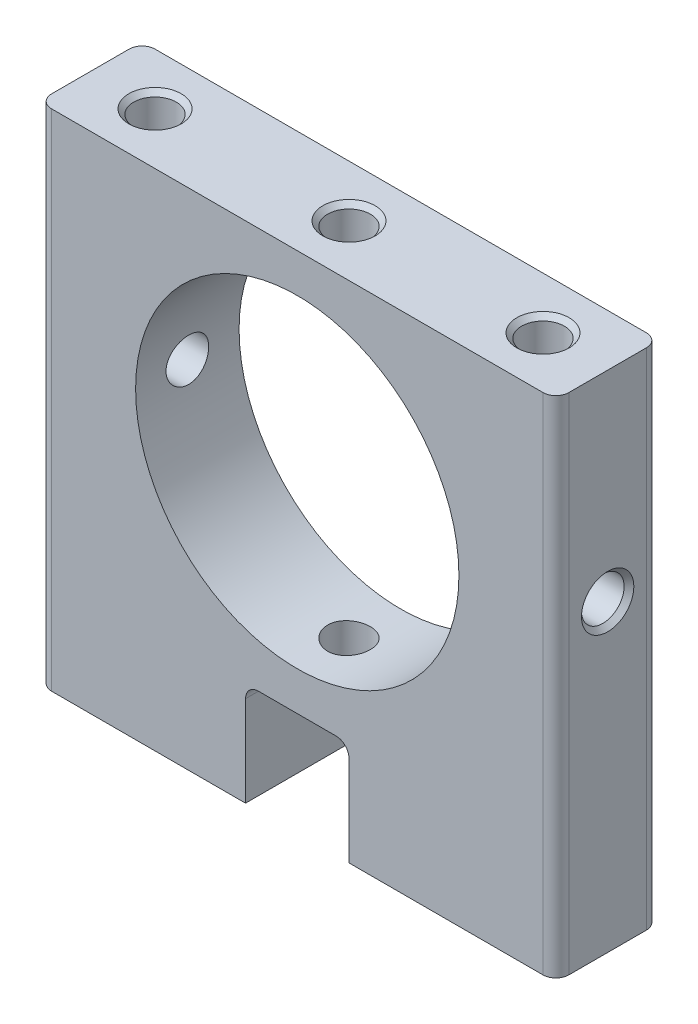
SolidWorks part; units mm, degrees
ref_plane "前视基准面" through (0, 0, 0) normal (0, 0, 1) x (1, 0, 0)
ref_plane "上视基准面" through (0, 0, 0) normal (0, 1, 0) x (1, 0, 0)
ref_plane "右视基准面" through (0, 0, 0) normal (1, 0, 0) x (0, 0, -1)
sketch "草图1" plane through (0, 0, 0) normal (0, 1, 0) x (1, 0, 0)
  line L1 (-20, 4) -> (20, 4)
  line L2 (-20, 4) -> (-20, -4)
  line L3 (-20, -4) -> (20, -4)
  line L4 (20, 4) -> (20, -4)
  line L5 (0, -4) -> (0, 4) construction
  line L6 (-20, 0) -> (20, 0) construction
  point P0 (0, 0)
  dimension "D1" = 8
  dimension "D2" = 40
extrude "凸台-拉伸1" add sketch "草图1" along normal blind 39
sketch "草图2" plane through (0, 39, 0) normal (0, 1, 0) x (1, 0, 0)
  line L0 (0, 4) -> (0, -4) construction
  line L1 (20, 4) -> (-20, 4) construction
  line L2 (-20, -4) -> (20, -4) construction
  line L3 (-20, 0) -> (20, 0) construction
  line L4 (-20, 4) -> (-20, -4) construction
  line L5 (20, -4) -> (20, 4) construction
  point P12 (-15, 0)
  point P13 (15, 0)
  dimension "D1" = 30
hole_wizard "M4 螺纹孔2" positions "草图5" profile "草图6" tap size "M4" standard "GB"
sketch "草图5" plane through (0, 39, 0) normal (0, 1, 0) x (1, 0, 0)
  point P0 (-15, 0)
  point P3 (15, 0)
cosmetic thread "孔螺蚊线2" parameters "D1"=6, "D2"=4
cosmetic thread "孔螺蚊线3" parameters "D1"=6, "D2"=4
sketch "草图6" plane through (-15, 39, 0) normal (1, 0, 0) x (0, 0, 1)
  line L0 (0, 0) -> (0, 9.0914)
  line L1 (0, 9.0914) -> (1.65, 8.1)
  line L2 (1.65, 8.1) -> (1.65, 0.375)
  line L3 (1.65, 0.375) -> (2.025, 0)
  line L5 (2.025, 0) -> (0, 0)
  line L6 (-1.65, 0.375) -> (-2.025, 0) construction
  line L10 (0, 9.0914) -> (-1.65, 8.1) construction
  line L11 (0, -6.35) -> (0, 107.95) construction
  dimension "螺纹孔钻头直径" = 3.3
  dimension "螺纹孔钻头深度" = 8.1
  dimension "近端锥形沉头孔直径" = 4.05
  dimension "近端锥形沉头孔角度" = 90
  dimension "导头角度" = 118
hole_wizard "M4 螺纹孔4" positions "草图9" profile "草图10" tap size "M4" standard "GB"
sketch "草图9" plane through (0, 0, 0) normal (0, -1, 0) x (-1, 0, 0)
  point P0 (15, 0)
  point P3 (-15, 0)
sketch "草图10" plane through (-15, 0, 0) normal (1, 0, 0) x (0, 0, -1)
  line L0 (0, 0) -> (0, 9.0914)
  line L1 (0, 9.0914) -> (1.65, 8.1)
  line L2 (1.65, 8.1) -> (1.65, 0.375)
  line L3 (1.65, 0.375) -> (2.025, 0)
  line L5 (2.025, 0) -> (0, 0)
  line L6 (-1.65, 0.375) -> (-2.025, 0) construction
  line L10 (0, 9.0914) -> (-1.65, 8.1) construction
  line L11 (0, -6.35) -> (0, 107.95) construction
  dimension "螺纹孔钻头直径" = 3.3
  dimension "螺纹孔钻头深度" = 8.1
  dimension "近端锥形沉头孔直径" = 4.05
  dimension "近端锥形沉头孔角度" = 90
  dimension "导头角度" = 118
cosmetic thread "孔螺蚊线5" parameters "D1"=6, "D2"=4
cosmetic thread "孔螺蚊线6" parameters "D1"=6, "D2"=4
sketch "草图11" plane through (0, 0, 4) normal (0, 0, 1) x (1, 0, 0)
  line L0 (0, 39) -> (0, 0) construction
  line L1 (-20, 39) -> (20, 39) construction
  line L2 (-20, 0) -> (20, 0) construction
  circle A0 centre (0, 23.5) radius 12.5
  dimension "D1" = 23.5
  dimension "D2" = 25
extrude "切除-拉伸1" cut sketch "草图11" against normal blind 39
hole_wizard "M4 螺纹孔5" positions "草图12" profile "草图13" tap size "M4" standard "GB" end condition through all
sketch "草图12" plane through (0, 39, 0) normal (0, 1, 0) x (1, 0, 0)
  point P0 (0, 0)
sketch "草图13" plane through (0, 39, 0) normal (1, 0, 0) x (0, 0, 1)
  line L0 (0, 0) -> (0, 39)
  line L1 (0, 39) -> (1.65, 39)
  line L2 (1.65, 39) -> (1.65, 0.375)
  line L3 (1.65, 0.375) -> (2.025, 0)
  line L5 (2.025, 0) -> (0, 0)
  line L6 (-1.65, 0.375) -> (-2.025, 0) construction
  line L11 (0, -6.35) -> (0, 107.95) construction
  dimension "通孔螺纹孔钻头直径" = 3.3
  dimension "通孔螺纹孔钻头深度" = 39
  dimension "近端锥形沉头孔直径" = 4.05
  dimension "近端锥形沉头孔角度" = 90
cosmetic thread "孔螺蚊线7" parameters "D2"=4
sketch "草图14" plane through (0, 0, 0) normal (0, -1, 0) x (1, 0, 0)
  line L0 (20, -4) -> (-20, -4) construction
  line L1 (-4, 4) -> (4, 4)
  line L2 (-4, 4) -> (-4, -4)
  line L3 (-4, -4) -> (4, -4)
  line L4 (4, 4) -> (4, -4)
  line L5 (0, -4) -> (0, 4) construction
  line L6 (-4, 0) -> (4, 0) construction
  point P0 (0, 0)
  dimension "D1" = 8
extrude "切除-拉伸2" cut sketch "草图14" against normal blind 8
sketch "草图15" plane through (20, 0, 0) normal (1, 0, 0) x (0, 0, -1)
  line L0 (0, 39) -> (0, 0) construction
  line L1 (4, 39) -> (-4, 39) construction
  line L2 (-4, 0) -> (4, 0) construction
  point P5 (0, 23.5)
  dimension "D1" = 23.5
hole_wizard "M4 螺纹孔6" positions "草图16" profile "草图17" tap size "M4" standard "GB" end condition through all
sketch "草图16" plane through (20, 0, 0) normal (1, 0, 0) x (0, 0, -1)
  point P0 (0, 23.5)
sketch "草图17" plane through (20, 23.5, 0) normal (0, 1, 0) x (0, 0, -1)
  line L0 (0, 0) -> (0, 40)
  line L1 (0, 40) -> (1.65, 40)
  line L2 (1.65, 40) -> (1.65, 0.375)
  line L3 (1.65, 0.375) -> (2.025, 0)
  line L5 (2.025, 0) -> (0, 0)
  line L6 (-1.65, 0.375) -> (-2.025, 0) construction
  line L11 (0, -6.35) -> (0, 107.95) construction
  dimension "通孔螺纹孔钻头直径" = 3.3
  dimension "通孔螺纹孔钻头深度" = 40
  dimension "近端锥形沉头孔直径" = 4.05
  dimension "近端锥形沉头孔角度" = 90
cosmetic thread "孔螺蚊线8" parameters "D2"=4
fillet "圆角1" radius 1 2 edges at (-4, 8, 0) (4, 8, 0)
fillet "圆角2" radius 1 4 edges at (20, 19.5, 4) (20, 19.5, -4) (-20, 19.5, 4) (-20, 19.5, -4)
sketch "草图18" plane through (0, 0, -4) normal (0, 0, -1) x (-1, 0, 0)
  circle A0 centre (0, 23.5) radius 12.5
  circle A1 centre (0, 23.5) radius 15
  dimension "D1" = 30
